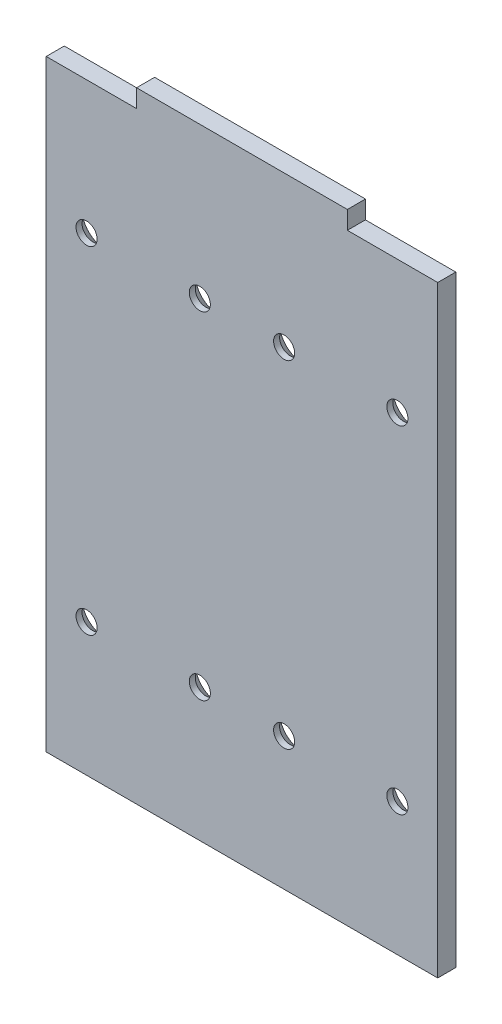
SolidWorks part; units mm, degrees
material "ABS"
ref_plane "Спереди" through (0, 0, 0) normal (0, 0, 1) x (1, 0, 0)
ref_plane "Сверху" through (0, 0, 0) normal (0, 1, 0) x (1, 0, 0)
ref_plane "Справа" through (0, 0, 0) normal (1, 0, 0) x (0, 0, -1)
sketch "Эскиз1" plane through (0, 0, 0) normal (0, 0, 1) x (1, 0, 0)
  line L1 (-32.5, -50) -> (32.5, -50)
  line L2 (-32.5, -50) -> (-32.5, 50)
  line L3 (-32.5, 50) -> (32.5, 50)
  line L4 (32.5, -50) -> (32.5, 50)
  line L5 (-32.5, -50) -> (32.5, 50) construction
  line L6 (-32.5, 50) -> (32.5, -50) construction
  line L7 (-17.5, 47) -> (17.5, 47)
  line L8 (-17.5, 47) -> (-17.5, 53)
  line L9 (-17.5, 53) -> (17.5, 53)
  line L10 (17.5, 47) -> (17.5, 53)
  line L11 (-17.5, 47) -> (17.5, 53) construction
  line L12 (-17.5, 53) -> (17.5, 47) construction
  point P0 (0, 0)
  point P6 (0, 50)
  dimension "D1" = 3
  dimension "D2" = 35
  dimension "D3" = 15
  dimension "D4" = 100
extrude "Бобышка-Вытянуть1" add sketch "Эскиз1" along normal blind 3 contours L10 L7 L8 L3 L2 L1 L4 | L7 L10 L3 L8 | L3 L10 L9 L8
sketch "Эскиз2" plane through (0, 0, 3) normal (0, 0, 1) x (1, 0, 0)
  line L0 (0, 53) -> (0, -50) construction
  line L1 (-17.5, 53) -> (17.5, 53) construction
  line L2 (-32.5, -50) -> (32.5, -50) construction
  line L3 (-32.5, 0) -> (32.5, 0) construction
  line L4 (-32.5, -50) -> (-32.5, 50) construction
  line L5 (32.5, -50) -> (32.5, 50) construction
  line L6 (25.8, -27.95) -> (7, 27.95) construction
  line L7 (-25.8, 27.95) -> (-7, 27.95) construction
  line L8 (-25.8, 27.95) -> (-25.8, -27.95) construction
  line L9 (-25.8, -27.95) -> (-7, -27.95) construction
  line L10 (-7, 27.95) -> (-7, -27.95) construction
  line L11 (-25.8, 27.95) -> (-7, -27.95) construction
  line L12 (-25.8, -27.95) -> (-7, 27.95) construction
  line L13 (25.8, 27.95) -> (7, -27.95) construction
  line L14 (7, 27.95) -> (7, -27.95) construction
  line L15 (25.8, -27.95) -> (7, -27.95) construction
  line L16 (25.8, 27.95) -> (25.8, -27.95) construction
  line L17 (25.8, 27.95) -> (7, 27.95) construction
  circle A0 centre (-25.8, 27.95) radius 1.75
  circle A1 centre (-7, 27.95) radius 1.75
  circle A2 centre (7, 27.95) radius 1.75
  circle A3 centre (25.8, 27.95) radius 1.75
  circle A4 centre (-25.8, -27.95) radius 1.75
  circle A5 centre (-7, -27.95) radius 1.75
  circle A6 centre (7, -27.95) radius 1.75
  circle A7 centre (25.8, -27.95) radius 1.75
  point P12 (-16.4, 0)
  point P21 (16.4, 0)
  dimension "D4" = 3.5
  dimension "D1" = 18.8
  dimension "D2" = 55.9
  dimension "D3" = 7
extrude "Вырез-Вытянуть1" cut sketch "Эскиз2" against normal blind 10
chamfer "Фаска1" distance 2 angle 45 8 edges at (-24.05, 27.95, 0) (-5.25, 27.95, 0) (8.75, 27.95, 0) (27.55, 27.95, 0) (27.55, -27.95, 0) (8.75, -27.95, 0) (-5.25, -27.95, 0) (-24.05, -27.95, 0)
